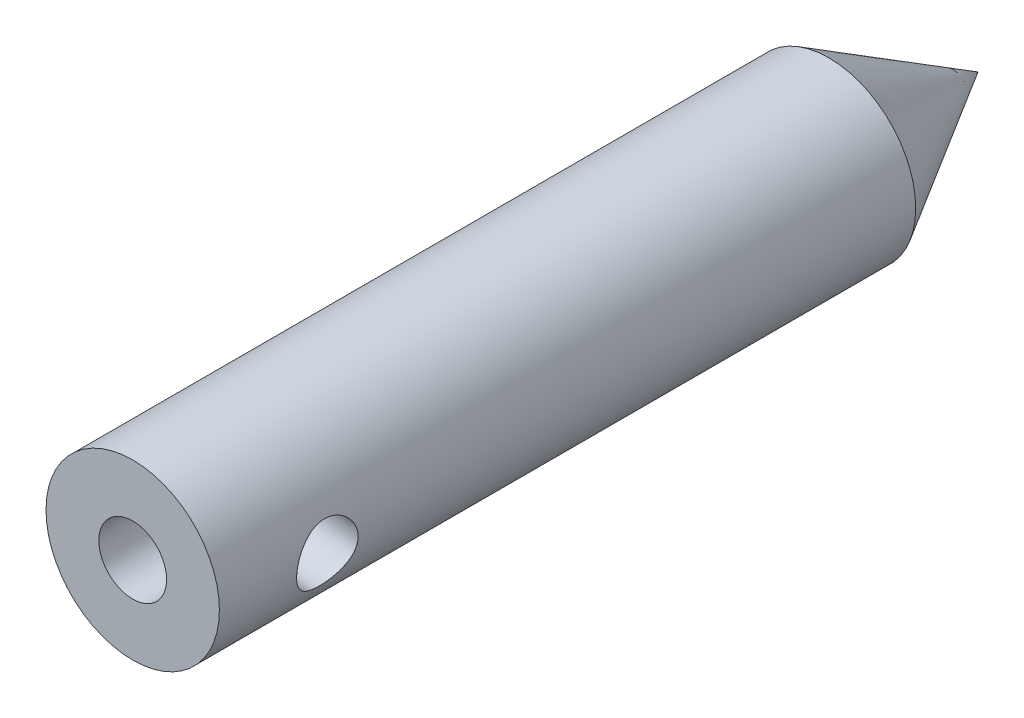
SolidWorks part; units mm, degrees
ref_plane "Front Plane" through (0, 0, 0) normal (0, 0, 1) x (1, 0, 0)
ref_plane "Top Plane" through (0, 0, 0) normal (0, 1, 0) x (1, 0, 0)
ref_plane "Right Plane" through (0, 0, 0) normal (1, 0, 0) x (0, 0, -1)
sketch "Sketch3" plane through (0, 0, 0) normal (0, 0, 1) x (1, 0, 0)
  circle A0 centre (0, 0) radius 3.2
  dimension "D1" = 6.4
extrude "Boss-Extrude2" add sketch "Sketch3" along normal blind 25.7
sketch "Sketch6" plane through (0, 0, 25.7) normal (0, 0, 1) x (1, 0, 0)
  circle A0 centre (0, 0) radius 1.25
  dimension "D1" = 2.5
extrude "Cut-Extrude1" cut sketch "Sketch6" against normal blind 25.7 and the other way through all
sketch "Sketch7" plane through (0, 0, 0) normal (0, 1, 0) x (1, 0, 0)
  line L0 (0, 0) -> (-3.2, 0)
  line L1 (-3.2, 0) -> (0, 5.5)
  line L2 (0, 5.5) -> (0, 0)
  dimension "D1" = 3.2
  dimension "D2" = 5.5
revolve "Revolve1" add sketch "Sketch7" angle 360 about L2
hole_wizard "Tap Drill for #4-40 Tap1" positions "3DSketch1" profile "Sketch8" hole size "#4-40" standard "ANSI Inch" end condition through all
sketch3d "3DSketch1"
  point P0 (3.1875, -0.2822, 21.7)
  dimension "D1" = 4
sketch "Sketch8" plane through (3.1875, -0.2822, 21.7) normal (0, 0, 1) x (0.0882, 0.9961, 0)
  line L0 (0, 0) -> (0, 6.6698)
  line L1 (0, 6.6698) -> (1.1303, 6.6698)
  line L2 (1.1303, 6.6698) -> (1.1303, 0)
  line L5 (1.1303, 0) -> (0, 0)
  line L11 (0, -6.35) -> (0, 107.95) construction
  dimension "Thru Hole Dia." = 2.2606
  dimension "Thru Hole Depth" = 6.6698
